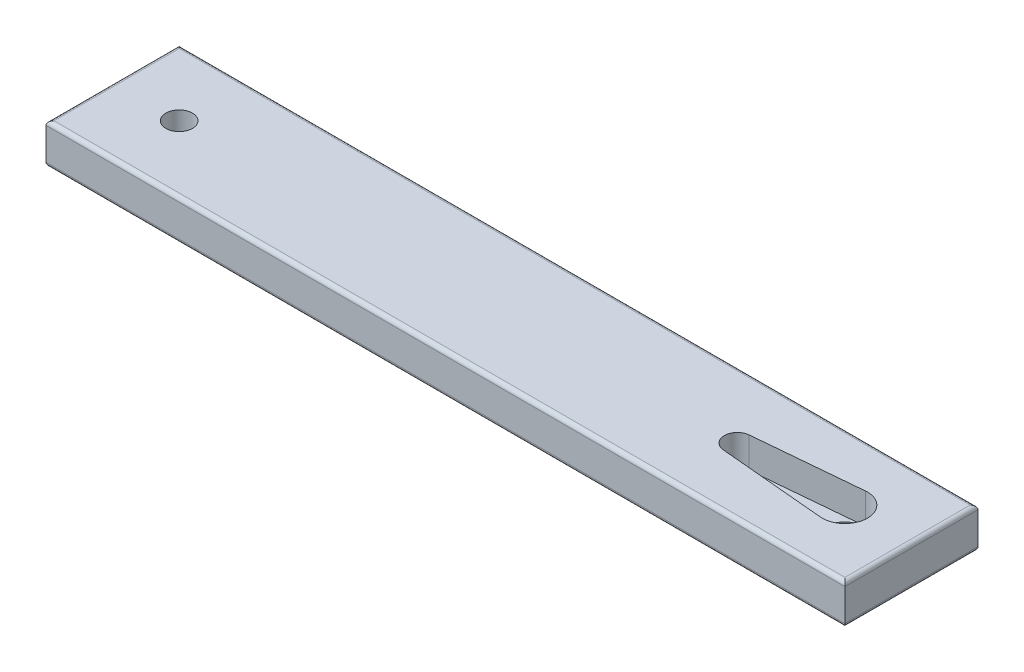
SolidWorks part; units mm, degrees
ref_plane "Front Plane" through (0, 0, 0) normal (0, 0, 1) x (1, 0, 0)
ref_plane "Top Plane" through (0, 0, 0) normal (0, 1, 0) x (1, 0, 0)
ref_plane "Right Plane" through (0, 0, 0) normal (1, 0, 0) x (0, 0, -1)
sketch "Sketch1" plane through (0, 0, 0) normal (0, 1, 0) x (1, 0, 0)
  line L1 (0, 0) -> (120, 0)
  line L2 (0, 0) -> (0, 20)
  line L3 (0, 20) -> (120, 20)
  line L4 (120, 0) -> (120, 20)
  dimension "D1" = 120
  dimension "D2" = 20
extrude "Boss-Extrude1" add sketch "Sketch1" along normal blind 6
sketch "Sketch2" plane through (0, 6, 0) normal (0, 1, 0) x (1, 0, 0)
  line L0 (120, 0) -> (120, 20) construction
  line L1 (93.6749, 11.9421) -> (109.6947, 13.3863)
  line L2 (93.6749, 8.0579) -> (109.6947, 6.6137)
  arc A0 (93.6749, 11.9421) -> (93.6749, 8.0579) centre (93.85, 10) ccw
  arc A1 (109.6947, 6.6137) -> (109.6947, 13.3863) centre (110, 10) ccw
  point P6 (120, 10)
  dimension "D3" = 3.9
  dimension "D4" = 6.8
  dimension "D1" = 16.15
  dimension "D2" = 10
extrude "Cut-Extrude1" cut sketch "Sketch2" against normal blind 4.6
sketch "Sketch3" plane through (0, 1.4, 0) normal (0, 1, 0) x (1, 0, 0)
  circle A0 centre (110, 10) radius 3.4
extrude "Cut-Extrude2" cut sketch "Sketch3" against normal blind 4.6
sketch "Sketch4" plane through (0, 6, 0) normal (0, 1, 0) x (1, 0, 0)
  line L0 (0, 20) -> (0, 0) construction
  circle A0 centre (10, 10) radius 2
  point P5 (0, 10)
  dimension "D1" = 4
  dimension "D2" = 10
extrude "Cut-Extrude3" cut sketch "Sketch4" against normal through all
fillet "Fillet1" radius 0.6 8 edges at (60, 0, 0) (0, 0, -10) (60, 0, -20) (120, 0, -10) (120, 6, -10) (60, 6, 0) (0, 6, -10) (60, 6, -20)
